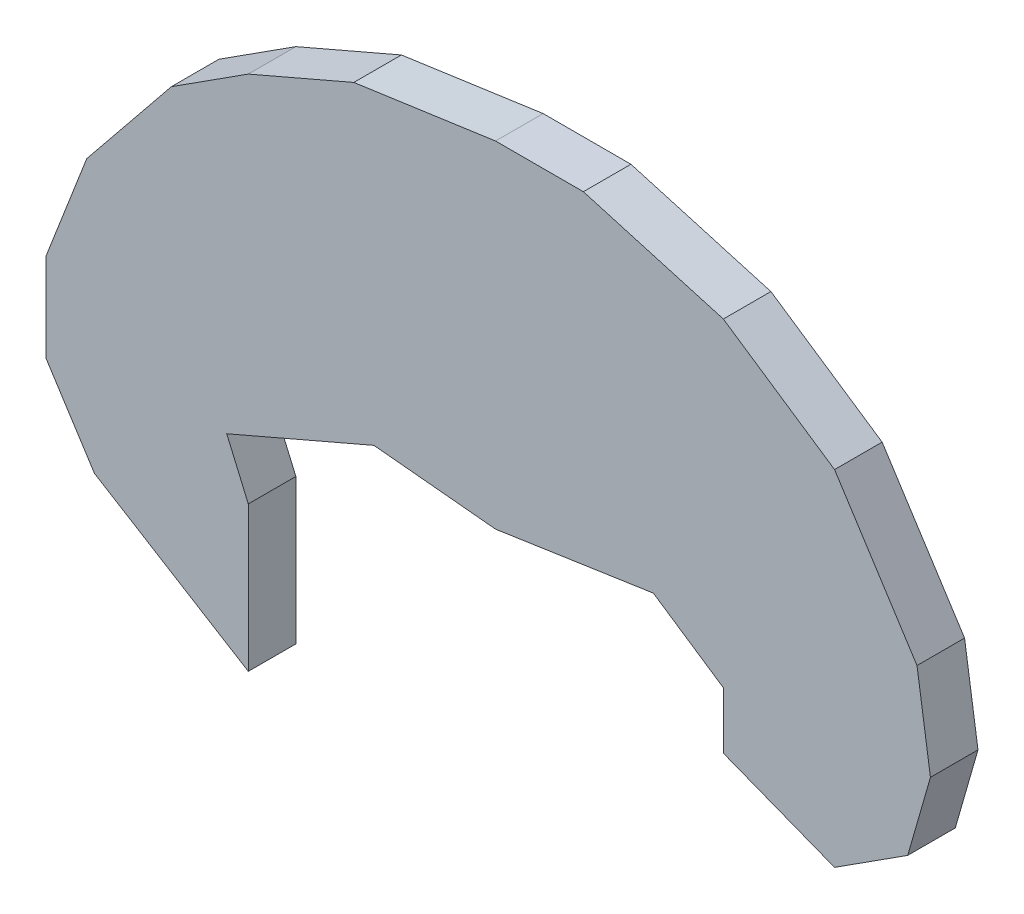
SolidWorks part; units mm, degrees
ref_plane "Спереди" through (0, 0, 0) normal (0, 0, 1) x (1, 0, 0)
ref_plane "Сверху" through (0, 0, 0) normal (0, 1, 0) x (1, 0, 0)
ref_plane "Справа" through (0, 0, 0) normal (1, 0, 0) x (0, 0, -1)
sketch "Эскиз3" plane through (0, 0, 0) normal (0, 0, 1) x (1, 0, 0)
  line L8 (-6.5143, 57.1713) -> (11.9469, 57.1713)
  line L15 (11.9469, 57.1713) -> (41.3758, 48.7054)
  line L16 (41.3758, 48.7054) -> (64.7576, 32.9832)
  line L17 (64.7576, 32.9832) -> (82.0924, 5.9731)
  line L18 (82.0924, 5.9731) -> (84.9144, -12.9743)
  line L19 (84.9144, -12.9743) -> (80.1386, -29.5758)
  line L20 (80.1386, -29.5758) -> (64.7576, -39.4472)
  line L21 (64.7576, -39.4472) -> (41.3758, -30.3508)
  line L22 (41.3758, -30.3508) -> (41.3758, -18.4249)
  line L23 (41.3758, -18.4249) -> (26.6613, -8.5619)
  line L24 (26.6613, -8.5619) -> (-6.5143, -13.503)
  line L25 (-6.5143, -13.503) -> (-32.0877, -11.0325)
  line L26 (-32.0877, -11.0325) -> (-63.0362, -24.3878)
  line L27 (-63.0362, -24.3878) -> (-58.5003, -34.899)
  line L28 (-58.5003, -34.899) -> (-58.5003, -56.1097)
  line L29 (-58.5003, -56.1097) -> (-58.5003, -65.3878)
  line L30 (-58.5003, -65.3878) -> (-90.8526, -45.5044)
  line L31 (-90.8526, -45.5044) -> (-101.032, -29.6434)
  line L32 (-101.032, -29.6434) -> (-101.032, -11.0325)
  line L33 (-101.032, -11.0325) -> (-92.4646, 10.9895)
  line L34 (-92.4646, 10.9895) -> (-74.6764, 32.9832)
  line L35 (-74.6764, 32.9832) -> (-58.5003, 43.3648)
  line L36 (-58.5003, 43.3648) -> (-36.3155, 52.9383)
  line L37 (-36.3155, 52.9383) -> (-6.5143, 57.1713)
  point P0 (-6.5143, 1.7494)
extrude "Бобышка-Вытянуть1" add sketch "Эскиз3" along normal blind 10
